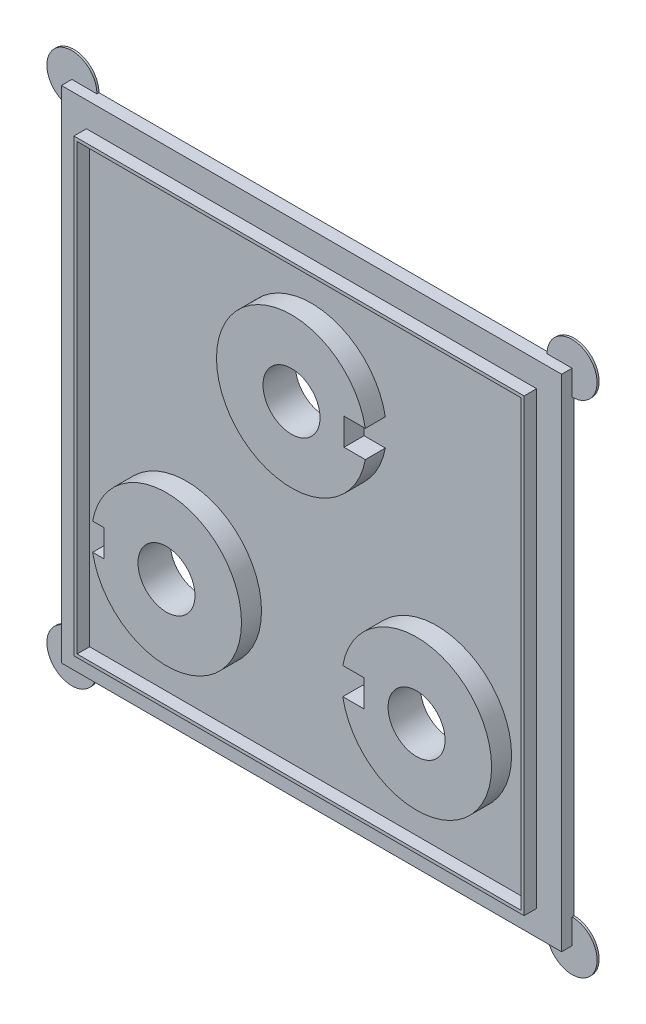
SolidWorks part; units mm, degrees
ref_plane "Front Plane" through (0, 0, 0) normal (0, 0, 1) x (1, 0, 0)
ref_plane "Top Plane" through (0, 0, 0) normal (0, 1, 0) x (1, 0, 0)
ref_plane "Right Plane" through (0, 0, 0) normal (1, 0, 0) x (0, 0, -1)
sketch "Sketch1" plane through (0, 0, 0) normal (0, 0, 1) x (1, 0, 0)
  line L1 (-31.75, -31.75) -> (31.75, -31.75)
  line L2 (-31.75, -31.75) -> (-31.75, 31.75)
  line L3 (-31.75, 31.75) -> (31.75, 31.75)
  line L4 (31.75, -31.75) -> (31.75, 31.75)
  line L5 (-31.75, -31.75) -> (31.75, 31.75) construction
  line L6 (-31.75, 31.75) -> (31.75, -31.75) construction
  point P0 (0, 0)
  dimension "D1" = 63.5
  dimension "D2" = 63.5
extrude "Boss-Extrude1" add sketch "Sketch1" along normal blind 1.5875
sketch "Sketch2" plane through (0, 0, 1.5875) normal (0, 0, 1) x (1, 0, 0)
  line L4 (28.175, 28.175) -> (-28.175, 28.175)
  line L5 (-28.175, 28.175) -> (-28.175, -28.175)
  line L6 (-28.175, -28.175) -> (28.175, -28.175)
  line L7 (28.175, -28.175) -> (28.175, 28.175)
  line L8 (28.575, -28.575) -> (28.575, 28.575)
  line L9 (28.575, 28.575) -> (-28.575, 28.575)
  line L10 (-28.575, 28.575) -> (-28.575, -28.575)
  line L11 (-28.575, -28.575) -> (28.575, -28.575)
  line L12 (28.575, -28.575) -> (28.575, 28.575)
  line L13 (28.575, 28.575) -> (-28.575, 28.575)
  line L14 (-28.575, 28.575) -> (-28.575, -28.575)
  line L15 (-28.575, -28.575) -> (28.575, -28.575)
  dimension "D1" = 3.175
  dimension "D2" = 0.4
extrude "Boss-Extrude2" add sketch "Sketch2" along normal blind 1.5875
sketch "Sketch3" plane through (0, 0, 1.5875) normal (0, 0, 1) x (1, 0, 0)
  line L0 (-15.875, -13.335) -> (15.875, -13.335) construction
  line L1 (0, -31.75) -> (0, 14.1613) construction
  line L2 (-31.75, -31.75) -> (31.75, -31.75) construction
  circle A0 centre (0, 14.1613) radius 8.5725 construction
  circle A1 centre (15.875, -13.335) radius 8.5725 construction
  circle A2 centre (-15.875, -13.335) radius 8.5725 construction
  circle A3 centre (-15.875, -13.335) radius 9.525
  circle A4 centre (0, 14.1613) radius 9.525
  circle A5 centre (15.875, -13.335) radius 9.525
  point P12 (0, -13.335)
  dimension "D1" = 17.145
  dimension "D2" = 17.145
  dimension "D3" = 17.145
  dimension "D5" = 19.05
  dimension "D6" = 19.05
  dimension "D7" = 19.05
  dimension "D4" = 31.75
  dimension "D8" = 18.415
  dimension "D9" = 31.75
extrude "Boss-Extrude4" add sketch "Sketch3" along normal blind 2.54
sketch "Sketch5" plane through (0, 0, 4.1275) normal (0, 0, 1) x (1, 0, 0)
  circle A0 centre (0, 14.1613) radius 3.6195
  circle A1 centre (15.875, -13.335) radius 3.6195
  circle A2 centre (-15.875, -13.335) radius 3.6195
  dimension "D1" = 7.239
  dimension "D2" = 7.239
  dimension "D3" = 7.239
extrude "Cut-Extrude2" cut sketch "Sketch5" against normal through all
sketch "Sketch6" plane through (0, 0, 4.1275) normal (0, 0, 1) x (1, 0, 0)
  line L1 (6.6675, 12.4468) -> (9.8425, 12.4468)
  line L2 (6.6675, 12.4468) -> (6.6675, 15.8758)
  line L3 (6.6675, 15.8758) -> (9.8425, 15.8758)
  line L4 (9.8425, 12.4468) -> (9.8425, 15.8758)
  line L5 (6.6675, 12.4468) -> (9.8425, 15.8758) construction
  line L6 (6.6675, 15.8758) -> (9.8425, 12.4468) construction
  line L7 (-26.9875, -15.0495) -> (-23.8125, -15.0495)
  line L8 (-26.9875, -15.0495) -> (-26.9875, -11.6205)
  line L9 (-26.9875, -11.6205) -> (-23.8125, -11.6205)
  line L10 (-23.8125, -15.0495) -> (-23.8125, -11.6205)
  line L11 (-26.9875, -15.0495) -> (-23.8125, -11.6205) construction
  line L12 (-26.9875, -11.6205) -> (-23.8125, -15.0495) construction
  line L13 (9.2075, -15.0495) -> (6.0325, -15.0495)
  line L14 (9.2075, -15.0495) -> (9.2075, -11.6205)
  line L15 (9.2075, -11.6205) -> (6.0325, -11.6205)
  line L16 (6.0325, -15.0495) -> (6.0325, -11.6205)
  line L17 (9.2075, -15.0495) -> (6.0325, -11.6205) construction
  line L18 (9.2075, -11.6205) -> (6.0325, -15.0495) construction
  circle A0 centre (0, 14.1613) radius 8.255 construction
  circle A1 centre (-15.875, -13.335) radius 8.255 construction
  circle A2 centre (15.875, -13.335) radius 8.255 construction
  circle A3 centre (-15.875, -13.335) radius 9.525 construction
  point P9 (8.255, 14.1613)
  point P14 (-25.4, -13.335)
  point P19 (7.62, -13.335)
  dimension "D1" = 16.51
  dimension "D2" = 16.51
  dimension "D3" = 16.51
  dimension "D4" = 3.175
  dimension "D5" = 3.429
  dimension "D6" = 3.429
  dimension "D7" = 3.175
  dimension "D8" = 3.175
  dimension "D9" = 3.429
extrude "Cut-Extrude3" cut sketch "Sketch6" against normal up to surface (2.54 mm away) up to face at (-9.525, 14.1613, 1.5875)
sketch "Sketch7" plane through (0, 0, 0) normal (0, 0, -1) x (-1, 0, 0)
  circle A0 centre (31.75, -31.75) radius 3.175
  circle A1 centre (-31.75, -31.75) radius 3.175
  circle A2 centre (-31.75, 31.75) radius 3.175
  circle A3 centre (31.75, 31.75) radius 3.175
  dimension "D1" = 6.35
  dimension "D2" = 6.35
  dimension "D3" = 6.35
  dimension "D4" = 6.35
extrude "Boss-Extrude5" add sketch "Sketch7" against normal blind 0.26
equation "\"0.23inmm\"=0.23"
